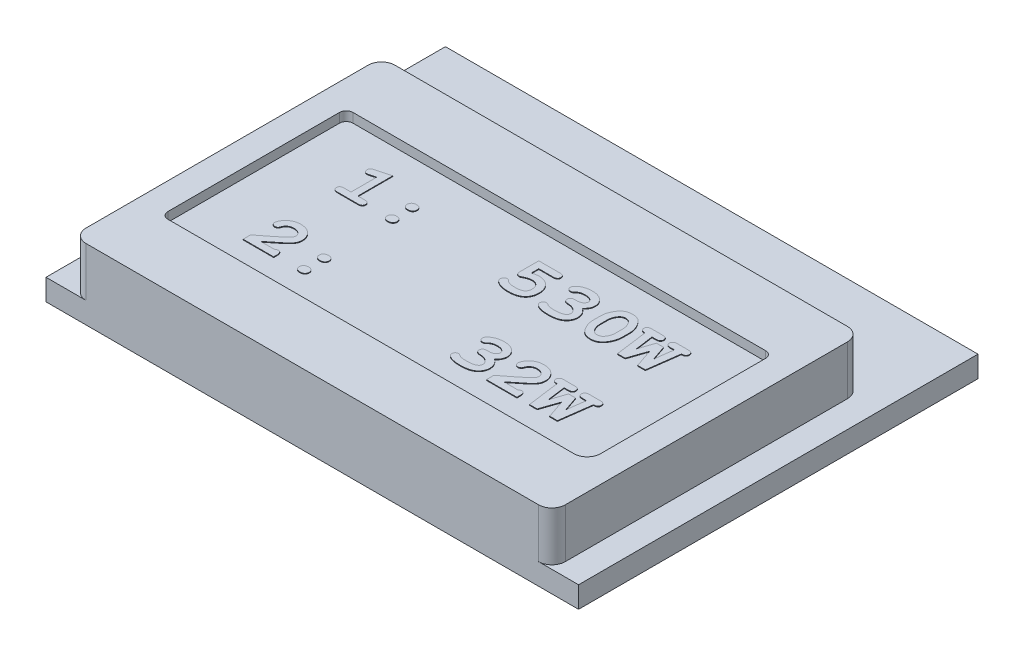
SolidWorks part; units mm, degrees
ref_plane "Front Plane" through (0, 0, 0) normal (0, 0, 1) x (1, 0, 0)
ref_plane "Top Plane" through (0, 0, 0) normal (0, 1, 0) x (1, 0, 0)
ref_plane "Right Plane" through (0, 0, 0) normal (1, 0, 0) x (0, 0, -1)
sketch "Sketch1" plane through (0, 0, 0) normal (0, 1, 0) x (1, 0, 0)
  line L1 (0, 30) -> (40, 30)
  line L2 (0, 30) -> (0, 0)
  line L3 (0, 0) -> (40, 0)
  line L4 (40, 30) -> (40, 0)
extrude "Boss-Extrude1" add sketch "Sketch1" against normal blind 1.6
sketch "Sketch5" plane through (0, 0, 0) normal (0, 1, 0) x (1, 0, 0)
  line L1 (2, 23.2) -> (38, 23.2)
  line L2 (2, 23.2) -> (2, 0)
  line L3 (2, 0) -> (38, 0)
  line L4 (38, 23.2) -> (38, 0)
  line L5 (4, 18.55) -> (36, 18.55)
  line L6 (4, 18.55) -> (4, 4.65)
  line L7 (4, 4.65) -> (36, 4.65)
  line L8 (36, 18.55) -> (36, 4.65)
extrude "Boss-Extrude2" add sketch "Sketch5" along normal blind 3.7
sketch "Sketch9" plane through (0, 0, 0) normal (0, 1, 0) x (1, 0, 0)
  line L1 (4, 18.55) -> (36, 18.55)
  line L2 (4, 18.55) -> (4, 4.65)
  line L3 (4, 4.65) -> (36, 4.65)
  line L4 (36, 18.55) -> (36, 4.65)
extrude "Boss-Extrude3" add sketch "Sketch9" along normal blind 3
fillet "Fillet5" radius 0.5 1 edges at (4, 3.35, -18.55)
fillet "Fillet6" radius 0.5 1 edges at (36, 3.35, -18.55)
fillet "Fillet7" radius 0.5 1 edges at (4, 3.35, -4.65)
fillet "Fillet8" radius 1 1 edges at (36, 3.35, -4.65)
fillet "Fillet9" radius 1 2 edges at (38, 1.85, -23.2)
fillet "Fillet10" radius 1 1 edges
fillet "Fillet11" radius 1 1 edges at (2, 1.85, -23.2)
sketch "Sketch10" plane through (0, 3, 0) normal (0, 1, 0) x (1, 0, 0)
  text T0 "1:  530W\r\n2:   32W" font "Courier New" height in points 13
extrude "Boss-Extrude4" add sketch "Sketch10" along normal blind 0.05
